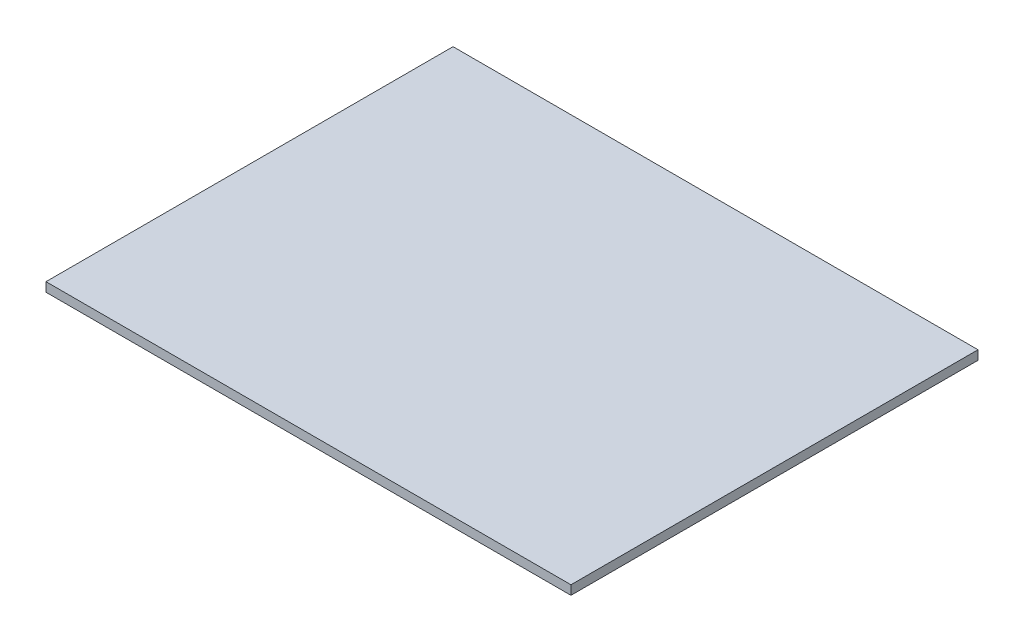
SolidWorks part; units mm, degrees
ref_plane "Front Plane" through (0, 0, 0) normal (0, 0, 1) x (1, 0, 0)
ref_plane "Top Plane" through (0, 0, 0) normal (0, 1, 0) x (1, 0, 0)
ref_plane "Right Plane" through (0, 0, 0) normal (1, 0, 0) x (0, 0, -1)
sketch "Sketch1" plane through (0, 0, 0) normal (0, 1, 0) x (1, 0, 0)
  line L1 (0, 0) -> (263.3435, 0)
  line L2 (0, 0) -> (0, 204.1914)
  line L3 (0, 204.1914) -> (263.3435, 204.1914)
  line L4 (263.3435, 0) -> (263.3435, 204.1914)
  line L5 (0, 0) -> (263.3435, 204.1914) construction
  line L6 (0, 204.1914) -> (263.3435, 0) construction
  point P4 (131.6717, 102.0957)
  dimension "D1" = 263.3435
  dimension "D2" = 204.1914
extrude "Boss-Extrude1" add sketch "Sketch1" along normal blind 4.6
equation "\"MDF\"= 4.8mm"
equation "\"Foamcore\"= 4.6mm"
equation "\"GMaterial\"= \"MDF\""
equation "\"PCB\" = 1.6mm"
equation "\"BaseWidth\" = 10in"
equation "\"SkidLength\" = 1in"
equation "\"SkidClearance\" = 0.4in"
equation "\"MotorMountLength\" = 2in"
equation "\"MotorMountWidth\" = \"GMaterial\""
equation "\"MotorMountHeight\" = 2.25in"
equation "\"UnoStackWidth\" = 77.4mm"
equation "\"UnoStackLength\" = 79.8mm"
equation "\"UnoStackHeight\" = 34.2mm"
equation "\"TallHexRiserHeight\" = 22.2mm"
equation "\"PingPongBallSize\" = 40mm"
equation "\"BarrelLength\" = 9in"
equation "\"BarrelSize\" = \"PingPongBallSize\""
equation "\"PlatformLength\" = 4in"
equation "\"PlatformWidth\" = 6in"
equation "\"WheelDiameter\"=2.99213"
equation "\"ServoMountHeight\"=2.49223"
equation "\"ServoGearHeight\" = 0.95330261in"
equation "\"ServoMountLength\"= 1.53774"
equation "\"PivotHoleRadius\"= 0.616358"
equation "\"PlatformMountHeight\" = 3.19"
equation "\"TensionOffSet\"= .3mm"
equation "\"MotorMountWedge\"=0.333333"
equation "\"LaserCutterOffset\"= .3mm"
equation "\"BumperWidth\"=11"
equation "\"PitcherWheelCompression\" = 2.5mm"
equation "\"BarrelToHopperDistance\" = 0.5405in"
equation "\"PitchingWheelWidth\" = 26.2mm"
equation "\"PitchingWheelDiameter\" = 65.5mm"
equation "\"PitchingWheelMountOffset\" = 8.4mm"
equation "\"PitchingWheelInnerDiameter\" = 45.5mm"
equation "\"PitchingWheelBoltShoulder\" = 4.5mm"
equation "\"BrassCouplingLength\" = 18mm"
equation "\"PitchingMotorHeight\" = 57.0mm"
equation "\"PitchingMotorShaftTopHeight\" = \"PitchingMotorHeight\" - 44.1mm"
equation "\"PitchingMotorBodyHeight\" = 38mm"
equation "\"PitchingMotorTopShoulderHeight\" = 40.6mm - \"PitchingMotorBodyHeight\" "
equation "\"PitchingMotorBottomShoulderHeight\" = 40.2mm - \"PitchingMotorBodyHeight\""
equation "\"PitchingMotorBottomShaftHeight\" = \"PitchingMotorHeight\" - \"PitchingMotorShaftTopHeight\" - \"PitchingMotorTopShoulderHeight\" - \"PitchingMotorBodyHeight\" - \"PitchingMotorBottomShoulderHeight\""
equation "\"PitchingMotorShaftDiameter\" = 2.2mm"
equation "\"PitchingMotorBodyDiameter\" = 27.4mm"
equation "\"PitchingMotorTopShoulderDiameter\" = 9.8mm"
equation "\"PitchingMotorBottomShoulderDiameter\" = 9.8mm"
equation "\"BrassCouplingHexSize\" = 12mm"
equation "\"BrassCouplingBoreSize\" = 3.17mm"
equation "\"PitchingMotorMountingHoleDistance\" = 16mm"
equation "\"Acrylic\" = 4.4mm"
equation "\"PitchingMotorDistance\" = \"PitchingWheelDiameter\" + \"PingPongBallSize\" - \"PitcherWheelCompression\"*2"
equation "\"PitchingMotorPlatformOffset\"=1"
equation "\"ServoPlatformOffset\"=1.64173"
equation "\"BallBearingDiameter\" = 22mm"
equation "\"BallBearingWidth\" = 9mm"
equation "\"BallBearingHexShoulder\" = 9mm - 5.9mm"
equation "\"BallBearingHexSize\" = .36in"
equation "\"PlatformMountFootLength\"=0.857143"
equation "\"WheelWidth\"= 26mm"
equation "\"ServoMountReductionBackHeight\"=2.25"
equation "\"PlatformBottomWidthThird\" =  0.857143in"
equation "\"PlatformMountBackReductionHeight\"= 2.5in"
equation "\"PlatformMountBackReductionWidth\"= 3/7in"
equation "\"PlatformMountFrontReductionWidth\" =  1.46226in"
equation "\"PlatformMountFrontReductionHeight\" = 2.5in"
equation "\"HopperLongWallLength\" = 8.646in"
equation "\"HopperShortWallLength\" = 0.9571in"
equation "\"HopperHeight\" = 3.50in - \"Foamcore\""
equation "\"HoperLongSlantLength\" = 7.064in"
equation "\"HopperBottomTemplateWidth\" = 8.03903165in"
equation "\"HopperBottomTemplateLength\" = 10.367854in"
equation "\"D1@Sketch1\"=\"HopperBottomTemplateLength\""
equation "\"D2@Sketch1\"=\"HopperBottomTemplateWidth\""
equation "\"D1@Boss-Extrude1\"=\"Foamcore\""
